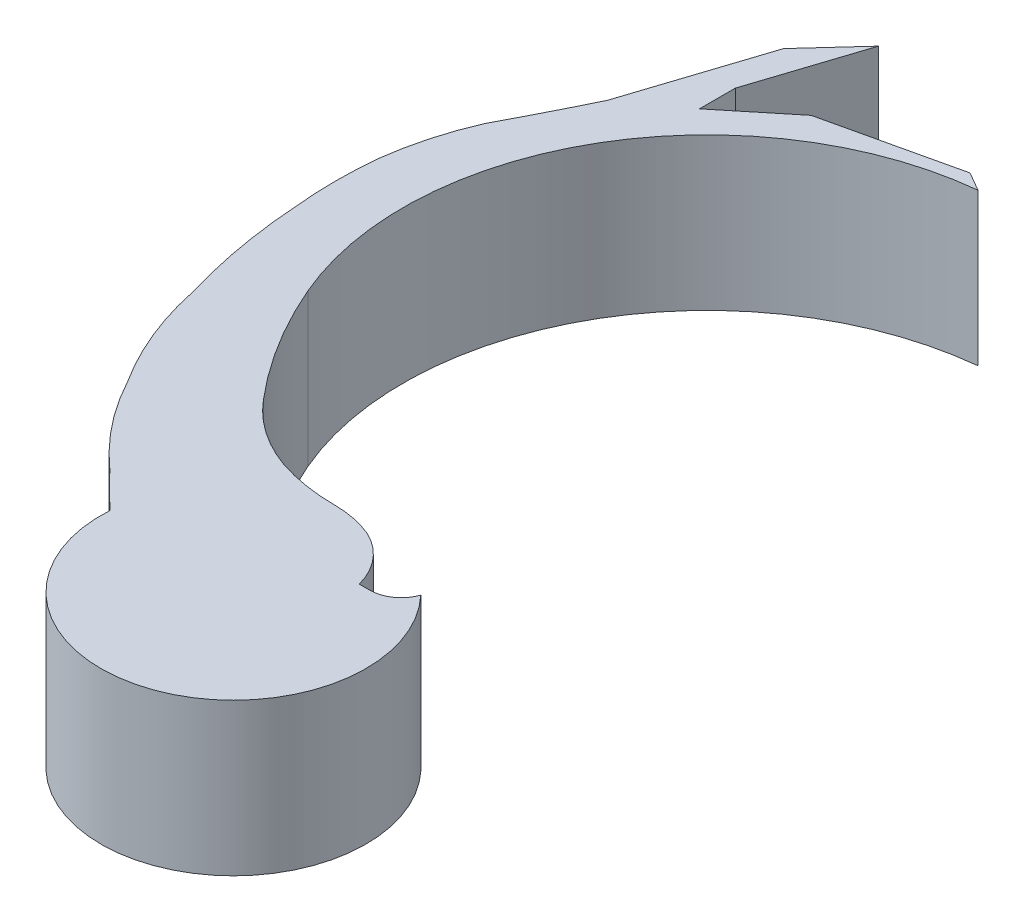
SolidWorks part; units mm, degrees
ref_plane "Front Plane" through (0, 0, 0) normal (0, 0, 1) x (1, 0, 0)
ref_plane "Top Plane" through (0, 0, 0) normal (0, 1, 0) x (1, 0, 0)
ref_plane "Right Plane" through (0, 0, 0) normal (1, 0, 0) x (0, 0, -1)
sketch "Sketch2" plane through (0, 0, 0) normal (0, 1, 0) x (1, 0, 0)
  line L0 (0, 0) -> (-35.9464, 0) construction
  line L1 (-35.9464, 0) -> (41.3976, 0) construction
  line L2 (41.3976, 0) -> (0, 0) construction
  line L3 (0, 0) -> (0, 18.7982) construction
  line L4 (0, 18.7982) -> (0, -23.465) construction
  circle A0 centre (0, 0) radius 20 construction
  circle A1 centre (0, 0) radius 23.465
sketch "Sketch4" plane through (0, 0, 0) normal (0, 1, 0) x (1, 0, 0)
  line L0 (-19.7005, -1.3216) -> (20.2972, -0.8891) construction
  circle A0 centre (0, 0) radius 23.4639 construction
  dimension "D1" = 40
sketch "Sketch5" plane through (0, 0, 0) normal (0, 1, 0) x (1, 0, 0)
  line L0 (-19.9303, -0.0851) -> (20.0695, 0.0365) construction
  dimension "D1" = 40
sketch "Sketch6" plane through (0, 0, 0) normal (0, 1, 0) x (1, 0, 0)
  circle A0 centre (-4.3374, 0.8589) radius 20
sketch "sungu kiri " plane through (0, 0, 0) normal (0, 1, 0) x (1, 0, 0)
  line L0 (-17.9037, 25.6768) -> (-20.2142, 18.582)
  line L1 (-20.2142, 18.582) -> (-20.2142, 16.2232)
  line L2 (-16.1729, 19.5215) -> (-7.6679, 21.4704)
  line L3 (-4.3302, -22.025) -> (-3.6458, -22.025)
  line L4 (-17.9037, 25.6768) -> (-20.8793, 22.4196)
  line L5 (-20.8793, 22.4196) -> (-23.726, 13.6785)
  line L6 (-23.3814, 7.2187) -> (-21.0655, 13.8643)
  line L8 (-21.0655, 13.8643) -> (-20.2142, 18.582)
  line L9 (-7.6679, 21.4704) -> (-6.4236, 20.7498)
  line L14 (-16.1729, 19.5215) -> (-20.2142, 16.2232)
  arc A0 (-4.3302, -22.025) -> (-6.9585, -18.8761) centre (-9.0425, -23.287) ccw
  arc A1 (-6.9585, -18.8761) -> (-9.6757, -18.3292) centre (-9.6898, -25.4217) ccw
  arc A2 (-9.6757, -18.3292) -> (-13.5956, -17.7015) centre (-9.6504, -5.6169) cw
  arc A3 (-13.5956, -17.7015) -> (-18.7296, -13.6646) centre (-10.3234, -8.257) cw
  arc A4 (-22.7226, -7.0141) -> (-17.1413, 16.2232) centre (-4.3374, 0.8589) cw
  arc A8 (-23.726, 13.6785) -> (-26.4444, 8.3095) centre (-176.3922, 87.6034) cw
  arc A9 (-26.4444, 8.3095) -> (-27.9369, 2.8451) centre (-7.9567, 0.3238) ccw
  arc A10 (-27.9369, 2.8451) -> (-27.9369, -2.4841) centre (-0.9166, 0.1805) ccw
  arc A11 (-27.9369, -2.4841) -> (-26.4444, -10.8627) centre (10.027, -0.0436) ccw
  arc A12 (-26.4444, -10.8627) -> (-23.4884, -18.0953) centre (-5.339, -6.4571) ccw
  arc A13 (-23.4884, -18.0953) -> (-19.0281, -23.7304) centre (-5.5688, -8.4944) ccw
  arc A14 (-19.0281, -23.7304) -> (-13.725, -28.6503) centre (23.0714, 16.3305) ccw
  circle A15 centre (-8.0208, -26.6118) radius 8.7178
  arc A16 (-3.6458, -22.025) -> (-1.6826, -20.6262) centre (-3.6458, -19.9479) ccw
  arc A18 (-18.7296, -13.6646) -> (-4.5283, -21.4375) centre (-2.7028, -1.2427) ccw construction
  arc A19 (-17.8504, -14.8335) -> (-22.7226, -7.0141) centre (5.1312, 4.9136) cw
  circle A20 centre (-4.3374, 0.8589) radius 20 construction
  arc A23 (-17.1413, 16.2232) -> (-6.4236, 20.7498) centre (-4.3374, 0.8589) cw
sketch "hjgjg" plane through (0, 0, 0) normal (0, 0, 1) x (1, 0, 0)
  line L0 (0, 0) -> (-35.9464, 0) construction
  line L1 (-35.9464, 0) -> (41.3976, 0) construction
  line L2 (41.3976, 0) -> (0, 0) construction
  line L3 (0, 0) -> (0, 18.7982) construction
  line L4 (0, 18.7982) -> (0, -23.465) construction
  circle A0 centre (0, 0) radius 20 construction
  circle A1 centre (0, 0) radius 23.465
extrude "Boss-Extrude1" add sketch "sungu kiri " along normal blind 10
